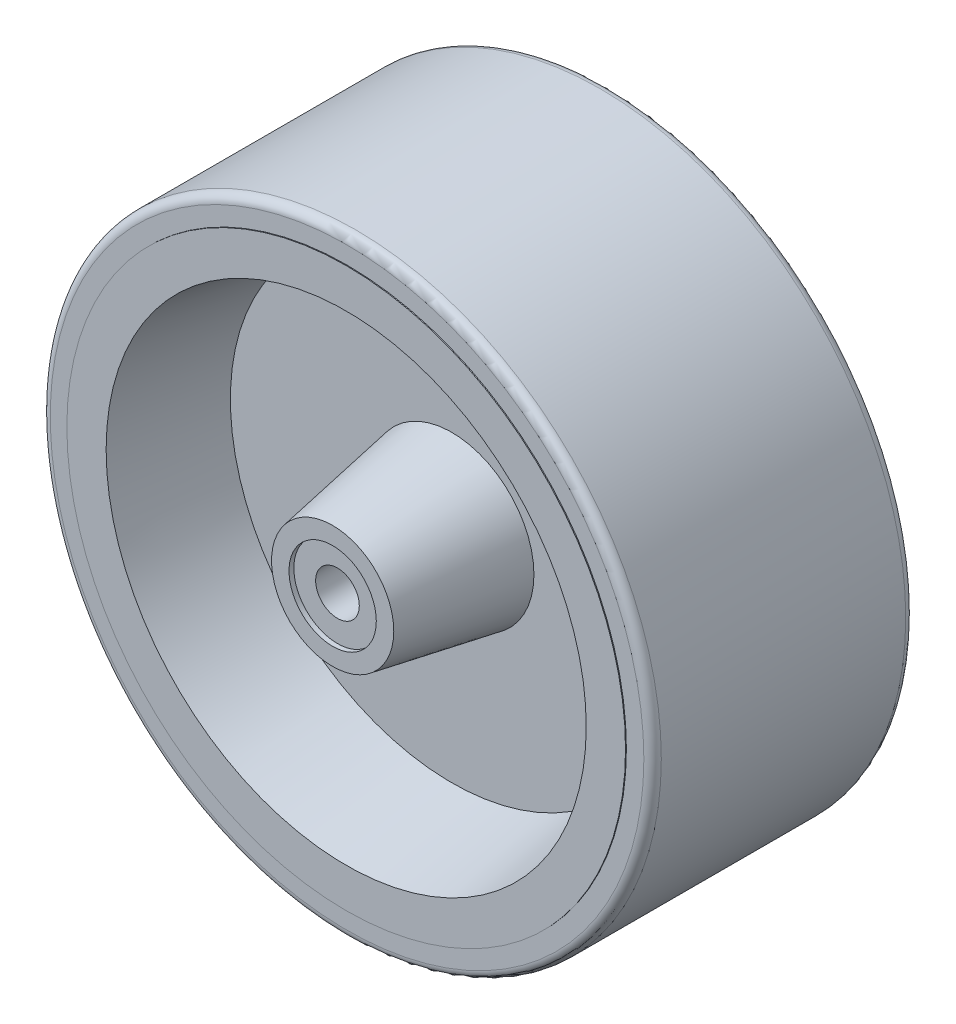
SolidWorks part; units mm, degrees
ref_plane "Front Plane" through (0, 0, 0) normal (0, 0, 1) x (1, 0, 0)
ref_plane "Top Plane" through (0, 0, 0) normal (0, 1, 0) x (1, 0, 0)
ref_plane "Right Plane" through (0, 0, 0) normal (1, 0, 0) x (0, 0, -1)
sketch "Sketch1" plane through (0, 0, 0) normal (0, 0, 1) x (1, 0, 0)
  circle A0 centre (0, 0) radius 88.9
  circle A1 centre (0, 0) radius 78.74
  dimension "D1" = 177.8
  dimension "D2" = 10.16
extrude "Boss-Extrude1" add sketch "Sketch1" along normal mid plane 76.2
fillet "Fillet1" radius 2.54 2 edges at (88.9, 0, -38.1) (88.9, 0, 38.1)
sketch "Sketch3" plane through (0, 0, 0) normal (0, 1, 0) x (1, 0, 0)
  line L0 (0, 0) -> (0, 60.9728) construction
  line L1 (0, 0) -> (-137.1098, 0) construction
  line L2 (0, 40.894) -> (0, -40.894)
  line L3 (0, -40.894) -> (-12.7, -40.894)
  line L4 (-12.7, -40.894) -> (-12.7, -42.291)
  line L5 (-12.7, -42.291) -> (-17.78, -42.291)
  line L6 (-17.78, -42.291) -> (-23.8934, -7.62)
  line L7 (-23.8934, -7.62) -> (-64.4308, -7.62)
  line L8 (-64.4308, -7.62) -> (-69.85, -38.354)
  line L9 (-69.85, -38.354) -> (-81.28, -38.354)
  line L10 (-81.28, -38.354) -> (-81.28, 38.354)
  line L11 (-12.7, 40.894) -> (-12.7, 42.291)
  line L12 (0, 40.894) -> (-12.7, 40.894)
  line L13 (-12.7, 42.291) -> (-17.78, 42.291)
  line L14 (-69.85, 38.354) -> (-81.28, 38.354)
  line L15 (-64.4308, 7.62) -> (-69.85, 38.354)
  line L16 (-23.8934, 7.62) -> (-64.4308, 7.62)
  line L17 (-17.78, 42.291) -> (-23.8934, 7.62)
  point P21 (-81.28, 0)
  dimension "D1" = 40.894
  dimension "D2" = 12.7
  dimension "D3" = 1.397
  dimension "D4" = 5.08
  dimension "D5" = 100
  dimension "D6" = 100
  dimension "D7" = 38.354
  dimension "D8" = 11.43
  dimension "D9" = 81.28
  dimension "D10" = 7.62
revolve "Revolve1" add sketch "Sketch3" angle 360 about L0
sketch "Sketch8" plane through (0, 0, 40.894) normal (0, 0, 1) x (1, 0, 0)
  circle A0 centre (0, 0) radius 6.35
  dimension "D1" = 12.7
extrude "Cut-Extrude1" cut sketch "Sketch8" against normal through all
